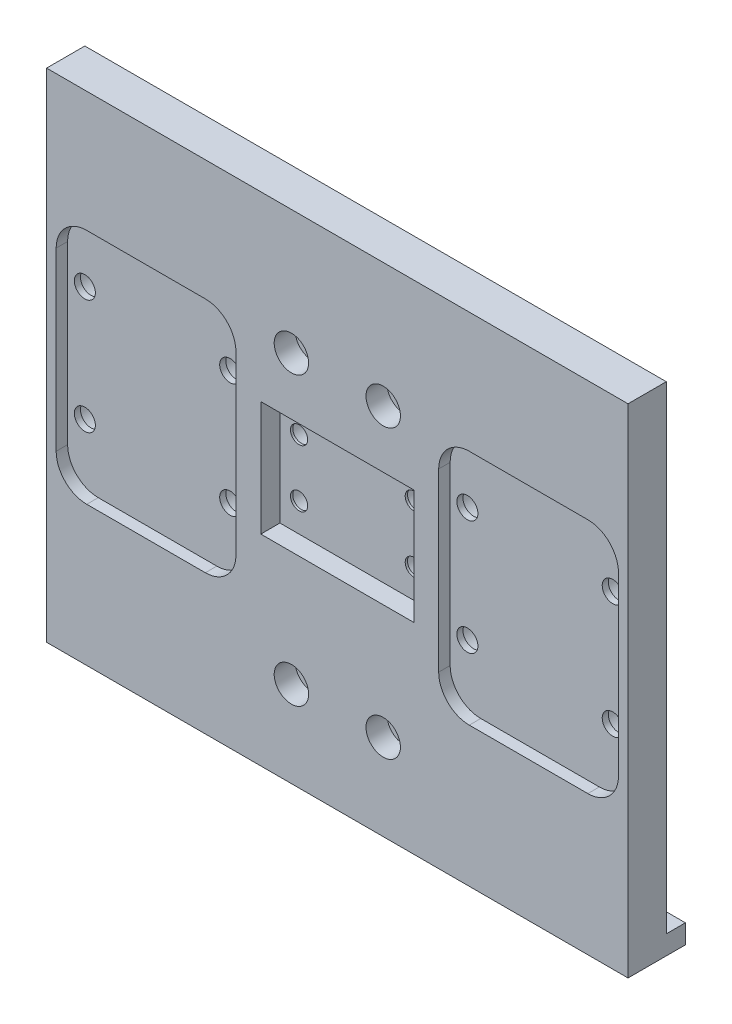
SolidWorks part; units mm, degrees
material "5754 (Alm. Plaka Malz.)"
ref_plane "Front Plane" through (0, 0, 0) normal (0, 0, 1) x (1, 0, 0)
ref_plane "Top Plane" through (0, 0, 0) normal (0, 1, 0) x (1, 0, 0)
ref_plane "Right Plane" through (0, 0, 0) normal (1, 0, 0) x (0, 0, -1)
sketch "Sketch3" plane through (0, 0, 0) normal (0, 0, 1) x (1, 0, 0)
  line L2 (-76, 62.5) -> (-76, -62.5)
  line L5 (-76, 0) -> (76, 0) construction
  line L6 (0, -5.5) -> (0, 5.5) construction
  line L9 (76, 62.5) -> (76, -62.5)
  line L12 (-76, 62.5) -> (76, 62.5)
  line L13 (-76, -62.5) -> (76, -62.5)
  line L14 (0, -108.0059) -> (0, 108.0059) construction
  point P12 (0, 0)
  dimension "D3" = 152
  dimension "D4" = 125
extrude "Boss-Extrude2" add sketch "Sketch3" along normal blind 10
sketch "Sketch5" plane through (0, 0, 10) normal (0, 0, 1) x (1, 0, 0)
  line L0 (76, 62.5) -> (-76, 62.5) construction
  line L1 (-12, 30) -> (12, 30) construction
  line L2 (-12, 30) -> (-12, -45) construction
  line L3 (-12, -45) -> (12, -45) construction
  line L4 (12, 30) -> (12, -45) construction
  line L6 (0, 30) -> (0, -45) construction
  circle A0 centre (-12, 30) radius 2.5
  circle A1 centre (12, 30) radius 2.5
  circle A2 centre (12, -45) radius 2.5
  circle A3 centre (-12, -45) radius 2.5
  point P0 (0, 0)
  dimension "D3" = 5
  dimension "D1" = 24
  dimension "D2" = 75
  dimension "D4" = 32.5
sketch "Sketch10" plane through (0, 0, 0) normal (0, 0, -1) x (-1, 0, 0)
  line L0 (-76, 0) -> (76, 0) construction
  line L1 (-15, 7.5) -> (15, 7.5) construction
  line L2 (-15, 7.5) -> (-15, -7.5) construction
  line L3 (-15, -7.5) -> (15, -7.5) construction
  line L4 (15, 7.5) -> (15, -7.5) construction
  line L7 (-76, -62.5) -> (-76, 62.5) construction
  line L8 (76, 62.5) -> (76, -62.5) construction
  circle A0 centre (-15, 7.5) radius 1.7
  circle A1 centre (-15, -7.5) radius 1.7
  circle A2 centre (15, -7.5) radius 1.7
  circle A3 centre (15, 7.5) radius 1.7
  dimension "D4" = 3.4
  dimension "D1" = 30
  dimension "D2" = 15
  dimension "D3" = 15
  dimension "D5" = 7.5
sketch "Çizim2" plane through (0, 0, 10) normal (0, 0, 1) x (1, 0, 0)
  line L5 (0, -62.5) -> (0, 62.5) construction
  line L10 (76, 62.5) -> (-76, 62.5) construction
  line L11 (76, 0) -> (-76, 0) construction
  line L12 (-76, 62.5) -> (-76, -62.5) construction
  line L14 (-34.5, -31) -> (-65.5, -31)
  line L15 (-26.5, -23) -> (-26.5, 23)
  line L16 (-34.5, 31) -> (-65.5, 31)
  line L17 (-73.5, -23) -> (-73.5, 23)
  line L18 (-26.5, -31) -> (-73.5, 31) construction
  line L19 (-26.5, 31) -> (-73.5, -31) construction
  line L20 (65.5, -31) -> (34.5, -31)
  line L21 (73.5, -23) -> (73.5, 23)
  line L22 (65.5, 31) -> (34.5, 31)
  line L23 (26.5, -23) -> (26.5, 23)
  line L24 (73.5, -31) -> (26.5, 31) construction
  line L25 (73.5, 31) -> (26.5, -31) construction
  arc A0 (65.5, -31) -> (73.5, -23) centre (65.5, -23) ccw
  arc A1 (73.5, 23) -> (65.5, 31) centre (65.5, 23) ccw
  arc A2 (34.5, 31) -> (26.5, 23) centre (34.5, 23) ccw
  arc A3 (34.5, -31) -> (26.5, -23) centre (34.5, -23) cw
  arc A4 (-34.5, -31) -> (-26.5, -23) centre (-34.5, -23) ccw
  arc A5 (-65.5, -31) -> (-73.5, -23) centre (-65.5, -23) cw
  arc A6 (-26.5, 23) -> (-34.5, 31) centre (-34.5, 23) ccw
  arc A7 (-65.5, 31) -> (-73.5, 23) centre (-65.5, 23) ccw
  point P0 (-50, 0)
  point P6 (0, 0)
  point P12 (50, 0)
  point P18 (0, 0)
  dimension "D7" = 8
  dimension "D1" = 47
  dimension "D2" = 50
  dimension "D3" = 62
  dimension "D4" = 62
  dimension "D5" = 47
  dimension "D6" = 50
extrude "Kes-Ekstrüzyon1" cut sketch "Çizim2" against normal blind 3
hole_wizard "CBORE for M5 Hex Socket Head Cap Screw1" positions "Çizim3" profile "Çizim4" counterbore size "M5" standard "Yilmaz_Standart"
sketch "Çizim3" plane through (0, 0, 10) normal (0, 0, 1) x (1, 0, 0)
  point P0 (-12, 30)
  point P3 (12, 30)
  point P6 (-12, -45)
  point P9 (12, -45)
sketch "Çizim4" plane through (-12, 30, 10) normal (1, 0, 0) x (0, -1, 0)
  line L0 (0, 0) -> (0, 16.7425)
  line L1 (0, 16.7425) -> (2.9, 15)
  line L2 (2.9, 15) -> (2.9, 5.5)
  line L3 (2.9, 5.5) -> (4.5, 5.5)
  line L4 (4.5, 5.5) -> (4.5, 0)
  line L5 (4.5, 0) -> (0, 0)
  line L10 (0, 16.7425) -> (-2.9, 15) construction
  line L11 (0, -6.35) -> (0, 107.95) construction
  dimension "Hole Dia." = 5.8
  dimension "Hole Depth" = 15
  dimension "C'Bore Dia." = 9
  dimension "C'Bore Depth" = 5.5
  dimension "Drill Angle" = 118
hole_wizard "CBORE for M5 Hex Socket Head Cap Screw2" positions "Sketch6" profile "Sketch7" counterbore size "M5" standard "ISO" end condition through all
sketch "Sketch6" plane through (0, 0, 0) normal (0, 0, 1) x (1, 0, 0)
  line L3 (76, -62.5) -> (76, 62.5) construction
  line L4 (-76, 62.5) -> (-76, -62.5) construction
  line L5 (-76, -62.5) -> (76, -62.5) construction
  point P0 (-69, 15)
  point P2 (-31, 15)
  point P4 (-69, -15)
  point P6 (-31, -15)
  point P8 (31, 15)
  point P10 (31, -15)
  point P12 (69, -15)
  point P14 (69, 15)
  dimension "D1" = 7
  dimension "D2" = 30
  dimension "D3" = 38
  dimension "D4" = 7
  dimension "D5" = 38
  dimension "D6" = 47.5
sketch "Sketch7" plane through (-69, 15, 0) normal (1, 0, 0) x (0, 1, 0)
  line L0 (0, 0) -> (0, 10)
  line L1 (0, 10) -> (2.75, 10)
  line L3 (2.75, 10) -> (2.75, 5.4)
  line L4 (2.75, 5.4) -> (5, 5.4)
  line L5 (5, 5.4) -> (5, 0)
  line L7 (5, 0) -> (0, 0)
  line L11 (0, -6.35) -> (0, 107.95) construction
  dimension "Thru Hole Dia." = 5.5
  dimension "Thru Hole Depth" = 10
  dimension "C'Bore Dia." = 10
  dimension "C'Bore Depth" = 5.4
hole_wizard "CBORE for M4 Hex Socket Head Cap Screw2" positions "Sketch11" profile "Sketch12" counterbore size "M4" standard "ISO" end condition through all
sketch "Sketch11" plane through (0, 0, 0) normal (0, 0, -1) x (-1, 0, 0)
  point P0 (-15, 7.5)
  point P3 (-15, -7.5)
  point P6 (15, 7.5)
  point P9 (15, -7.5)
sketch "Sketch12" plane through (15, 7.5, 0) normal (1, 0, 0) x (0, 1, 0)
  line L0 (0, 0) -> (0, 10)
  line L1 (0, 10) -> (2.25, 10)
  line L3 (2.25, 10) -> (2.25, 4.4)
  line L4 (2.25, 4.4) -> (4, 4.4)
  line L5 (4, 4.4) -> (4, 0)
  line L7 (4, 0) -> (0, 0)
  line L11 (0, -6.35) -> (0, 107.95) construction
  dimension "Thru Hole Dia." = 4.5
  dimension "Thru Hole Depth" = 10
  dimension "C'Bore Dia." = 8
  dimension "C'Bore Depth" = 4.4
sketch "Sketch13" plane through (0, 0, 10) normal (0, 0, 1) x (1, 0, 0)
  line L1 (20, -15) -> (-20, -15)
  line L2 (20, -15) -> (20, 15)
  line L3 (20, 15) -> (-20, 15)
  line L4 (-20, -15) -> (-20, 15)
  line L5 (20, -15) -> (-20, 15) construction
  line L6 (20, 15) -> (-20, -15) construction
  point P0 (0, 0)
  dimension "D1" = 40
  dimension "D2" = 30
extrude "Cut-Extrude1" cut sketch "Sketch13" against normal blind 5
sketch "Sketch14" plane through (76, 0, 0) normal (-1, 0, 0) x (0, 0, 1)
  line L5 (0, 62.5) -> (0, -62.5) construction
  line L6 (10, -62.5) -> (-5, -62.5)
  line L7 (10, -62.5) -> (10, -67.5)
  line L8 (10, -67.5) -> (-5, -67.5)
  line L9 (-5, -62.5) -> (-5, -67.5)
  dimension "D1" = 5
  dimension "D2" = 5
extrude "Boss-Extrude3" add sketch "Sketch14" against normal up to surface (152 mm away)
